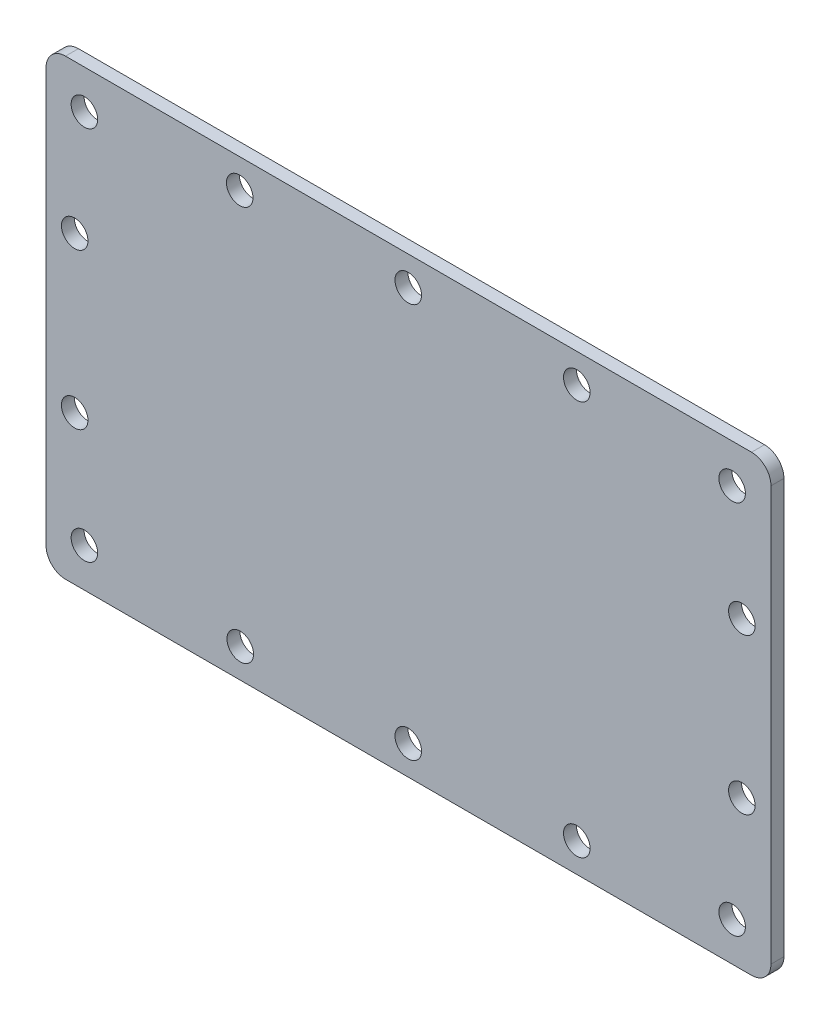
SolidWorks part; units mm, degrees
material "PUR"
ref_plane "Front Plane" through (0, 0, 0) normal (0, 0, 1) x (1, 0, 0)
ref_plane "Top Plane" through (0, 0, 0) normal (0, 1, 0) x (1, 0, 0)
ref_plane "Right Plane" through (0, 0, 0) normal (1, 0, 0) x (0, 0, -1)
sketch "Sketch1" plane through (0, 0, 0) normal (0, 0, 1) x (1, 0, 0)
  line L1 (-90.1915, 7.9323) -> (21.8085, 7.9323)
  line L2 (-90.1915, 7.9323) -> (-90.1915, -62.0677)
  line L3 (-90.1915, -62.0677) -> (21.8085, -62.0677)
  line L4 (21.8085, 7.9323) -> (21.8085, -62.0677)
  dimension "D1" = 112
  dimension "D2" = 70
extrude "Boss-Extrude1" add sketch "Sketch1" along normal blind 2
fillet "Fillet1" radius 3 4 edges at (-90.1915, -62.0677, 1) (-90.1915, 7.9323, 1) (21.8085, -62.0677, 1) (21.8085, 7.9323, 1)
sketch "Sketch2" plane through (0, 0, 2) normal (0, 0, 1) x (1, 0, 0)
  circle A0 centre (-84.2723, -56.0677) radius 2.05
  circle A1 centre (-85.7723, -39.0677) radius 2.05
  circle A2 centre (-85.7723, -15.0677) radius 2.05
  circle A3 centre (-84.2723, 1.9323) radius 2.05
  circle A4 centre (-60.2723, 3.4323) radius 2.05
  circle A5 centre (-60.1915, -57.5677) radius 2.05
  circle A6 centre (-34.2319, -57.5677) radius 2.05
  circle A7 centre (-34.2319, 3.4323) radius 2.05
  circle A8 centre (-8.1915, 3.4323) radius 2.05
  circle A9 centre (-8.1915, -57.5677) radius 2.05
  circle A10 centre (15.8085, -56.0677) radius 2.05
  circle A11 centre (17.3085, -39.0677) radius 2.05
  circle A12 centre (17.3085, -15.0677) radius 2.05
  circle A13 centre (15.8085, 1.9323) radius 2.05
extrude "Cut-Extrude1" cut sketch "Sketch2" against normal blind 3
